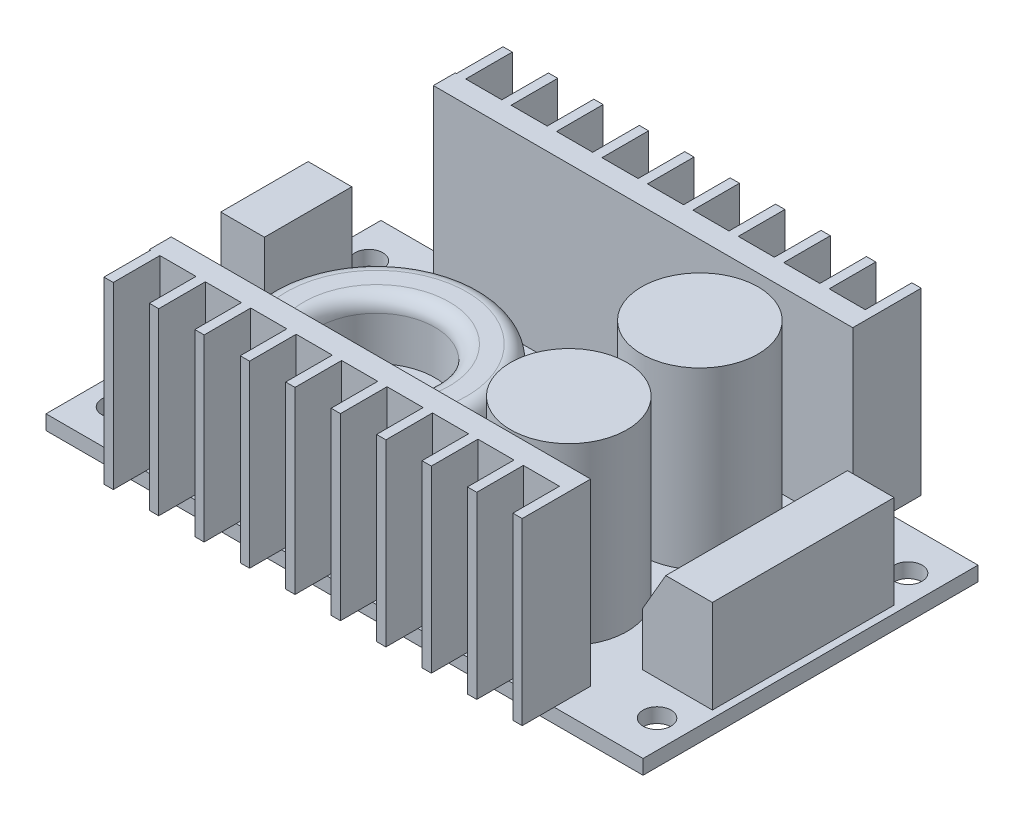
SolidWorks part; units mm, degrees
ref_plane "Front Plane" through (0, 0, 0) normal (0, 0, 1) x (1, 0, 0)
ref_plane "Top Plane" through (0, 0, 0) normal (0, 1, 0) x (1, 0, 0)
ref_plane "Right Plane" through (0, 0, 0) normal (1, 0, 0) x (0, 0, -1)
sketch "Sketch1" plane through (0, 0, 0) normal (0, 1, 0) x (1, 0, 0)
  line L1 (-32.5437, 18.2562) -> (32.5437, 18.2562)
  line L2 (-32.5437, 18.2562) -> (-32.5437, -18.2563)
  line L3 (-32.5437, -18.2563) -> (32.5437, -18.2563)
  line L4 (32.5437, 18.2562) -> (32.5437, -18.2563)
  line L5 (-32.5437, 18.2562) -> (32.5437, -18.2563) construction
  line L6 (-32.5437, -18.2563) -> (32.5437, 18.2562) construction
  point P0 (0, 0)
  dimension "D1" = 36.5125
  dimension "D2" = 65.0875
extrude "Boss-Extrude1" add sketch "Sketch1" along normal blind 1.5875
sketch "Sketch2" plane through (0, 1.5875, 0) normal (0, 1, 0) x (1, 0, 0)
  line L0 (0, 14.2875) -> (0, 0) construction
  line L1 (-22.86, 16.6687) -> (22.86, 16.6688)
  line L2 (-22.86, 16.6687) -> (-22.86, 14.2875)
  line L3 (-22.86, 14.2875) -> (22.86, 14.2875)
  line L4 (22.86, 16.6688) -> (22.86, 14.2875)
  line L5 (32.5437, 18.2562) -> (-32.5437, 18.2562) construction
  dimension "D1" = 2.3813
  dimension "D2" = 45.72
  dimension "D3" = 1.5875
extrude "Boss-Extrude2" add sketch "Sketch2" along normal blind 19.558
sketch "Sketch3" plane through (0, 0, -16.6687) normal (0, 0, -1) x (-1, 0, 0)
  line L0 (-22.86, 1.5875) -> (22.86, 1.5875) construction
  line L1 (-22.86, 21.1455) -> (-21.844, 21.1455)
  line L2 (-22.86, 21.1455) -> (-22.86, 1.5875)
  line L3 (-22.86, 1.5875) -> (-21.844, 1.5875)
  line L4 (-21.844, 21.1455) -> (-21.844, 1.5875)
  dimension "D1" = 1.016
extrude "Boss-Extrude3" add sketch "Sketch3" along normal blind 5.08
pattern_linear "LPattern1" count 10 spacing 4.953 along (-1, 0, 0) of "Boss-Extrude3"
sketch "Sketch4" plane through (0, 1.5875, 0) normal (0, 1, 0) x (1, 0, 0)
  line L0 (-32.5437, 0) -> (32.5437, 0) construction
  line L1 (-32.5437, 18.2562) -> (-32.5437, -18.2563) construction
  line L2 (32.5437, -18.2563) -> (32.5437, 18.2562) construction
  line L3 (13.335, 14.2875) -> (13.335, 0) construction
  line L4 (-22.86, 14.2875) -> (22.86, 14.2875) construction
  line L5 (22.86, 14.2875) -> (22.86, 21.7488) construction
  circle A0 centre (13.335, 7.1437) radius 6.35
  dimension "D2" = 12.7
  dimension "D1" = 9.525
extrude "Boss-Extrude4" add sketch "Sketch4" along normal blind 19.05
sketch "Sketch5" plane through (0, 1.5875, 0) normal (0, 1, 0) x (1, 0, 0)
  line L0 (32.5437, -18.2563) -> (32.5437, 18.2562) construction
  line L1 (32.5437, 18.2562) -> (22.86, 18.2562) construction
  line L2 (0.0635, 18.2562) -> (0, -18.2563) construction
  line L3 (2.032, 18.2562) -> (-1.905, 18.2562) construction
  line L4 (-32.5437, -18.2563) -> (32.5437, -18.2563) construction
  circle A0 centre (29.4957, 13.6842) radius 1.524
  circle A1 centre (-29.3845, 13.7867) radius 1.524
  dimension "D1" = 3.048
  dimension "D2" = 4.572
  dimension "D3" = 3.048
extrude "Cut-Extrude1" cut sketch "Sketch5" against normal blind 19.05
mirror "Mirror1" about plane through (0, 0, 0) normal (0, 0, 1) of "Boss-Extrude4", "LPattern1", "Boss-Extrude2", "Cut-Extrude1", "Boss-Extrude3"
sketch "Sketch6" plane through (0, 1.5875, 0) normal (0, 1, 0) x (1, 0, 0)
  line L0 (-32.5437, 0) -> (32.5437, 0) construction
  line L1 (-32.5437, 18.2562) -> (-32.5437, -18.2563) construction
  line L2 (32.5437, -18.2563) -> (32.5437, 18.2562) construction
  circle A0 centre (-14.7637, 0) radius 11.43
  circle A1 centre (-14.7637, 0) radius 6.35
  dimension "D1" = 12.7
  dimension "D2" = 22.86
  dimension "D3" = 17.78
extrude "Boss-Extrude5" add sketch "Sketch6" along normal blind 6.35
fillet "Fillet1" radius 1.5875 2 edges at (-14.7637, 7.9375, 11.43) (-14.7637, 7.9375, 6.35)
sketch "Sketch7" plane through (0, 1.5875, 0) normal (0, 1, 0) x (1, 0, 0)
  line L0 (-32.5437, 0) -> (32.5437, 0) construction
  line L1 (-32.5437, 18.2562) -> (-32.5437, -18.2563) construction
  line L2 (32.5437, -18.2563) -> (32.5437, 18.2562) construction
  line L4 (24.13, -9.906) -> (31.75, -9.906)
  line L5 (24.13, -9.906) -> (24.13, 9.906)
  line L6 (24.13, 9.906) -> (31.75, 9.906)
  line L7 (31.75, -9.906) -> (31.75, 9.906)
  line L8 (24.13, -9.906) -> (31.75, 9.906) construction
  line L9 (24.13, 9.906) -> (31.75, -9.906) construction
  point P6 (27.94, 0)
  dimension "D1" = 7.62
  dimension "D2" = 19.812
  dimension "D3" = 0.7937
extrude "Boss-Extrude6" add sketch "Sketch7" along normal blind 10.16
chamfer "Chamfer1" distance 2.54 angle 60 1 edges at (24.13, 11.7475, 0)
sketch "Sketch8" plane through (0, 1.5875, 0) normal (0, 1, 0) x (1, 0, 0)
  line L0 (-32.5437, 18.2562) -> (-32.5437, -18.2563) construction
  line L1 (-31.75, 9.525) -> (-26.9875, 9.525)
  line L2 (-31.75, 9.525) -> (-31.75, 0)
  line L3 (-31.75, 0) -> (-26.9875, 0)
  line L4 (-26.9875, 9.525) -> (-26.9875, 0)
  line L6 (-26.9875, 0) -> (0, 0) construction
  dimension "D1" = 4.7625
  dimension "D2" = 9.525
  dimension "D3" = 0.7937
extrude "Boss-Extrude7" add sketch "Sketch8" along normal blind 10.3187
